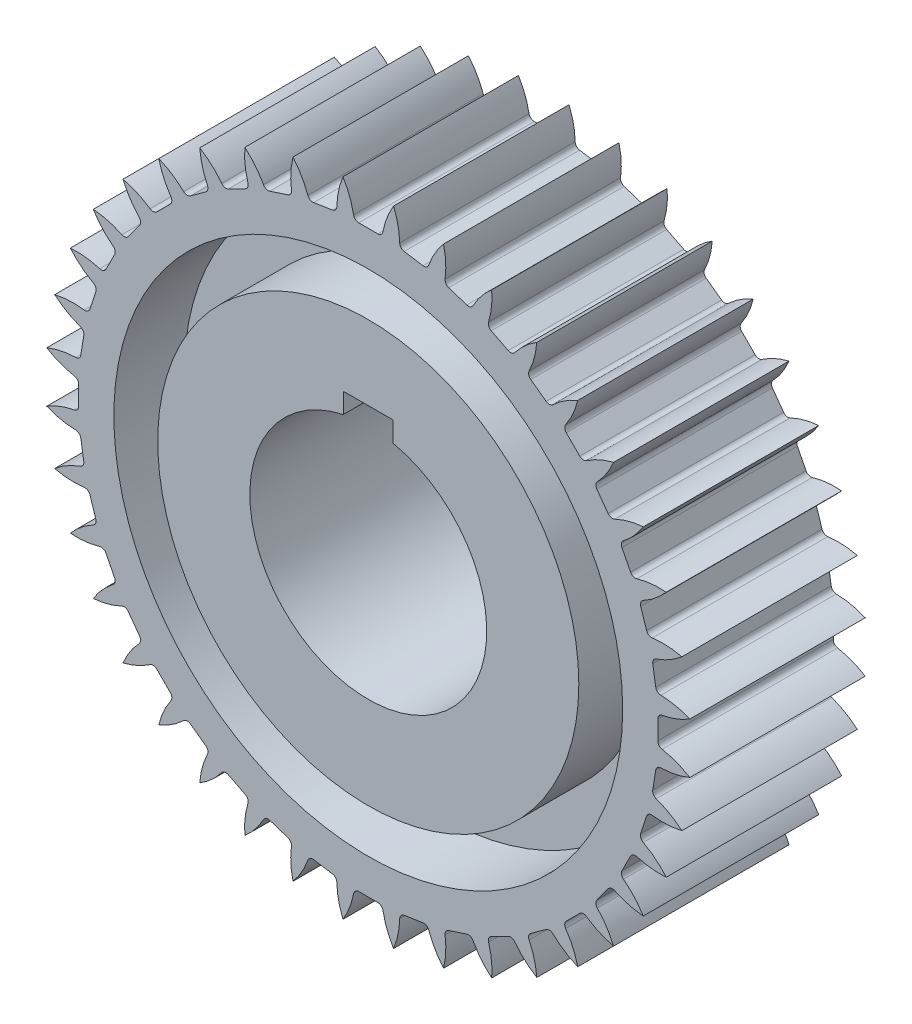
SolidWorks part; units mm, degrees
ref_plane "Front Plane" through (0, 0, 0) normal (0, 0, 1) x (1, 0, 0)
ref_plane "Top Plane" through (0, 0, 0) normal (0, 1, 0) x (1, 0, 0)
ref_plane "Right Plane" through (0, 0, 0) normal (1, 0, 0) x (0, 0, -1)
sketch "Sketch1" plane through (0, 0, 0) normal (0, 0, 1) x (1, 0, 0)
  circle A0 centre (0, 0) radius 18.75
  dimension "D1" = 37.5
extrude "Boss-Extrude1" add sketch "Sketch1" along normal blind 10
sketch "Sketch2" plane through (0, 0, 10) normal (0, 0, 1) x (1, 0, 0)
  line L0 (0, 0) -> (0, 5.75) construction
  line L1 (0, 6.75) -> (0, 12.5528) construction
  line L2 (-1.4217, 7.75) -> (1.4217, 7.75)
  line L3 (-1.4217, 7.75) -> (-1.4217, 6.5986)
  line L5 (1.4217, 7.75) -> (1.4217, 6.5986)
  arc A0 (-1.4217, 6.5986) -> (1.4217, 6.5986) centre (0, 0) ccw
  point P3 (0, 6.75)
  dimension "D1" = 13.5
extrude "Cut-Extrude1" cut sketch "Sketch2" against normal through all
sketch "Sketch3" plane through (0, 0, 10) normal (0, 0, 1) x (1, 0, 0)
  circle A0 centre (0, 0) radius 14.5
  circle A1 centre (0, 0) radius 12
  dimension "D1" = 29
  dimension "D2" = 24
extrude "Cut-Extrude2" cut sketch "Sketch3" against normal blind 4
sketch "Sketch4" plane through (0, 0, 0) normal (0, 0, -1) x (-1, 0, 0)
  circle A0 centre (0, 0) radius 12
  circle A1 centre (0, 0) radius 14.5
  dimension "D1" = 29
  dimension "D2" = 24
extrude "Cut-Extrude3" cut sketch "Sketch4" against normal blind 4
sketch "Sketch5" plane through (0, 0, 10) normal (0, 0, 1) x (1, 0, 0)
  line L0 (0, 0) -> (0, 27.3386) construction
  line L1 (-0.5427, 16.502) -> (0.5427, 16.502)
  arc A0 (0.8378, 16.7484) -> (2.8784, 19.782) centre (5.3244, 15.9335) cw
  arc A1 (-0.8378, 16.7484) -> (-2.8784, 19.782) centre (-5.3244, 15.9335) ccw
  arc A2 (-2.8784, 19.782) -> (2.8784, 19.782) centre (0, 2.0136) cw
  arc A3 (0.5427, 16.502) -> (0.8378, 16.7484) centre (0.5427, 16.802) ccw
  arc A4 (-0.5427, 16.502) -> (-0.8378, 16.7484) centre (-0.5427, 16.802) cw
  point P8 (0, 16.502)
  point P13 (0.8, 16.502)
  point P16 (-0.8, 16.502)
  dimension "D3" = 4.56
  dimension "D4" = 18
  dimension "D5" = 0.3
  dimension "D1" = 0.8
  dimension "D2" = 3.28
extrude "Cut-Extrude4" cut sketch "Sketch5" against normal through all
pattern_circular "CirPattern1" count 40 over 360 about axis through (0, 0, 0) along (0, 0, 1) of "Cut-Extrude4"
